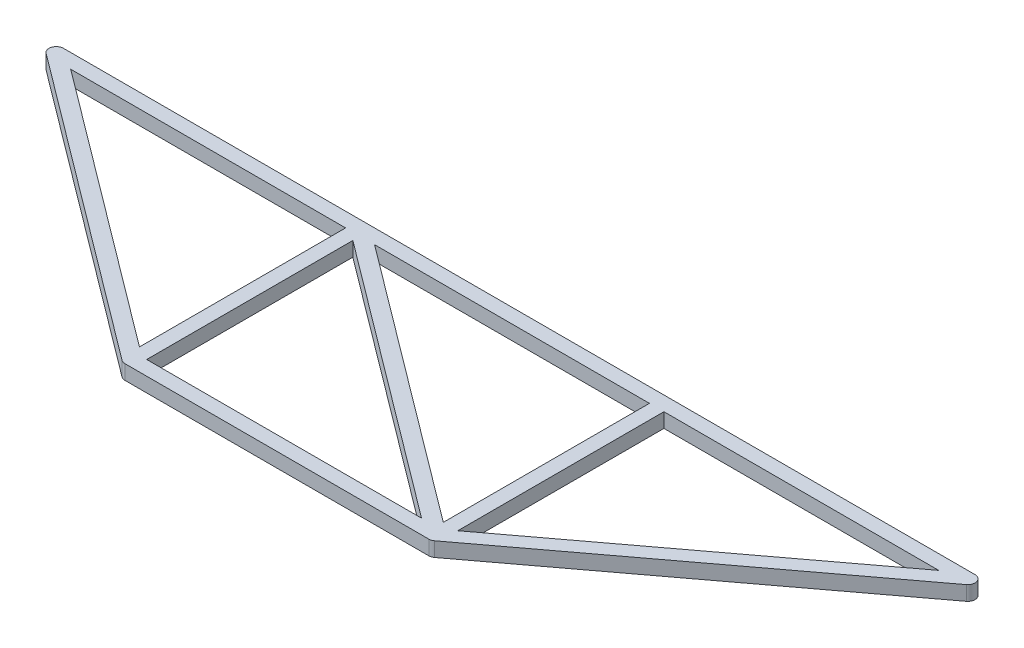
SolidWorks part; units mm, degrees
material "AISI 1020"
ref_plane "Front Plane" through (0, 0, 0) normal (0, 0, 1) x (1, 0, 0)
ref_plane "Top Plane" through (0, 0, 0) normal (0, 1, 0) x (1, 0, 0)
ref_plane "Right Plane" through (0, 0, 0) normal (1, 0, 0) x (0, 0, -1)
sketch "Sketch1" plane through (0, 0, 0) normal (0, 1, 0) x (1, 0, 0)
  line L0 (0, 0) -> (400, 0) construction
  line L1 (400, 0) -> (400, -300) construction
  line L2 (400, -300) -> (0, 0) construction
  line L3 (400, -300) -> (800, -300) construction
  line L10 (800, -300) -> (400, 0) construction
  line L11 (400, -300) -> (400, 0) construction
  line L12 (800, -300) -> (800, 0) construction
  line L13 (800, 0) -> (400, 0) construction
  line L14 (800, -300) -> (1200, 0) construction
  line L15 (1200, 0) -> (800, 0) construction
  line L16 (0, 9.54) -> (400, 9.54) construction
  line L17 (400, 9.54) -> (800, 9.54) construction
  line L18 (800, 9.54) -> (1200, 9.54) construction
  line L19 (400, -309.54) -> (800, -309.54) construction
  line L20 (400, -290.46) -> (800, -290.46) construction
  line L21 (790.46, -300) -> (790.46, 0) construction
  line L22 (809.54, -300) -> (809.54, 0) construction
  line L23 (409.54, -300) -> (409.54, 0) construction
  line L24 (390.46, -300) -> (390.46, 0) construction
  line L25 (1205.724, -7.632) -> (805.724, -307.632) construction
  line L26 (1194.276, 7.632) -> (794.276, -292.368) construction
  line L27 (-5.724, -7.632) -> (394.276, -307.632) construction
  line L28 (5.724, 7.632) -> (405.724, -292.368) construction
  line L29 (0, -9.54) -> (1200, -9.54) construction
  line L30 (405.8576, 7.53) -> (805.8576, -292.47) construction
  line L31 (394.276, -7.632) -> (794.276, -307.632) construction
  circle A0 centre (0, 0) radius 9.54 construction
  circle A1 centre (400, 0) radius 9.54 construction
  circle A2 centre (800, 0) radius 9.54 construction
  circle A3 centre (1200, 0) radius 9.54 construction
  circle A4 centre (800, -300) radius 9.54 construction
  circle A5 centre (400, -300) radius 9.54 construction
  dimension "D3" = 19.08
  dimension "D1" = 400
  dimension "D2" = 300
  dimension "D4" = 19.08
  dimension "D5" = 19.08
sketch "Sketch15" plane through (0, 0, 0) normal (0, 1, 0) x (1, 0, 0)
  line L0 (0, 9.54) -> (1200, 9.54)
  line L1 (1205.724, -7.632) -> (805.724, -307.632)
  line L2 (800, -309.54) -> (400, -309.54)
  line L3 (394.276, -307.632) -> (-5.724, -7.632)
  line L4 (390.46, -280.92) -> (390.46, -9.54)
  line L5 (390.46, -300) -> (390.46, 0) construction
  line L6 (5.724, 7.632) -> (405.724, -292.368) construction
  line L7 (0, -9.54) -> (1200, -9.54) construction
  line L8 (390.46, -9.54) -> (28.62, -9.54)
  line L9 (28.62, -9.54) -> (390.46, -280.92)
  line L10 (409.54, -19.08) -> (409.54, -290.46)
  line L13 (409.54, -300) -> (409.54, 0) construction
  line L15 (394.276, -7.632) -> (794.276, -307.632) construction
  line L16 (400, -290.46) -> (800, -290.46) construction
  line L17 (409.54, -290.46) -> (771.38, -290.46)
  line L18 (771.38, -290.46) -> (409.54, -19.08)
  line L19 (790.46, -280.9219) -> (428.6175, -9.54)
  line L20 (790.46, -300) -> (790.46, 0) construction
  line L21 (405.8576, 7.53) -> (805.8576, -292.47) construction
  line L22 (428.6175, -9.54) -> (790.46, -9.54)
  line L23 (790.46, -9.54) -> (790.46, -280.9219)
  line L24 (809.54, -280.92) -> (1171.38, -9.54)
  line L25 (809.54, -300) -> (809.54, 0) construction
  line L26 (1194.276, 7.632) -> (794.276, -292.368) construction
  line L27 (1171.38, -9.54) -> (809.54, -9.54)
  line L28 (809.54, -9.54) -> (809.54, -280.92)
  arc A0 (-5.724, -7.632) -> (0, 9.54) centre (0, 0) cw
  arc A1 (394.276, -307.632) -> (400, -309.54) centre (400, -300) ccw
  arc A2 (800, -309.54) -> (805.724, -307.632) centre (800, -300) ccw
  arc A3 (1205.724, -7.632) -> (1200, 9.54) centre (1200, 0) ccw
extrude "Boss-Extrude1" add sketch "Sketch15" along normal blind 19.08
